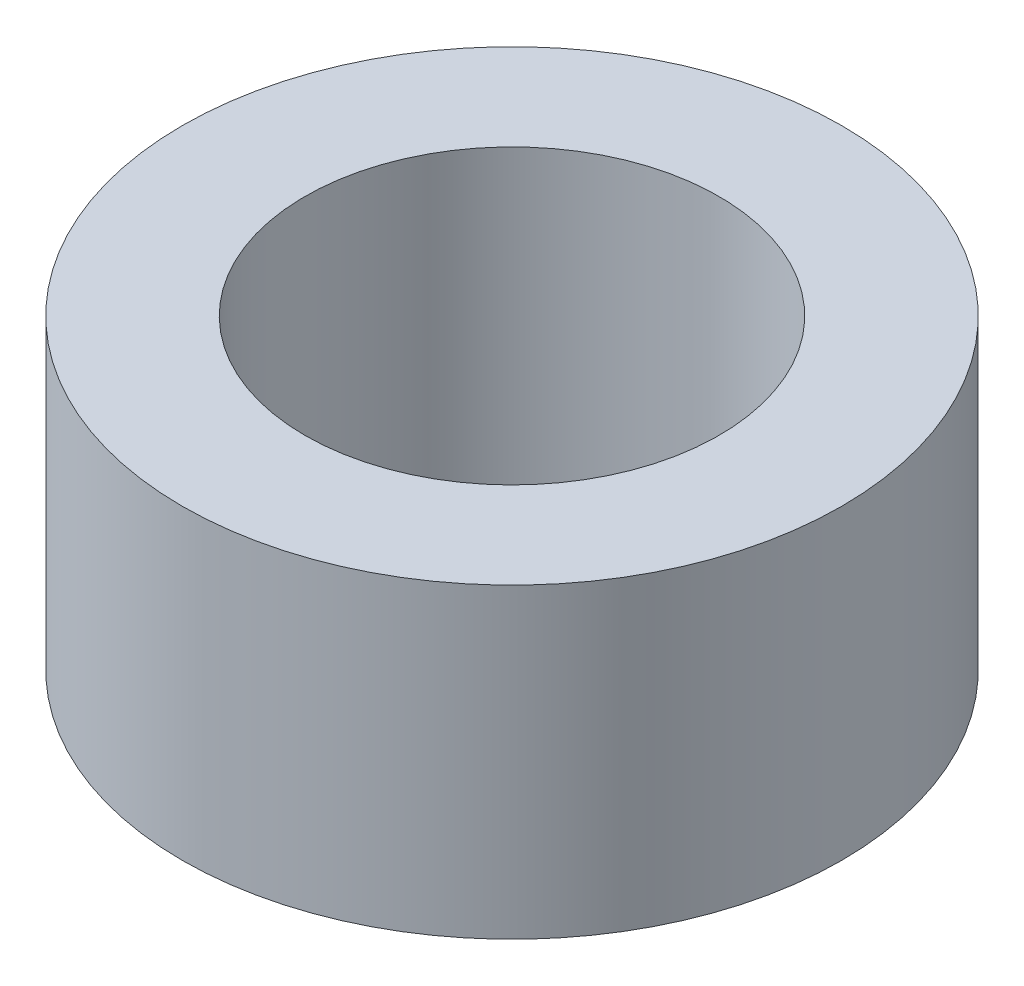
SolidWorks part; units mm, degrees
ref_plane "Front Plane" through (0, 0, 0) normal (0, 0, 1) x (1, 0, 0)
ref_plane "Top Plane" through (0, 0, 0) normal (0, 1, 0) x (1, 0, 0)
ref_plane "Right Plane" through (0, 0, 0) normal (1, 0, 0) x (0, 0, -1)
sketch "Sketch1" plane through (0, 0, 0) normal (0, 1, 0) x (1, 0, 0)
  circle A0 centre (0, 0) radius 3.375
  circle A1 centre (0, 0) radius 5.375
  dimension "D1" = 6.75
  dimension "D2" = 2
extrude "Boss-Extrude1" add sketch "Sketch1" along normal blind 5
